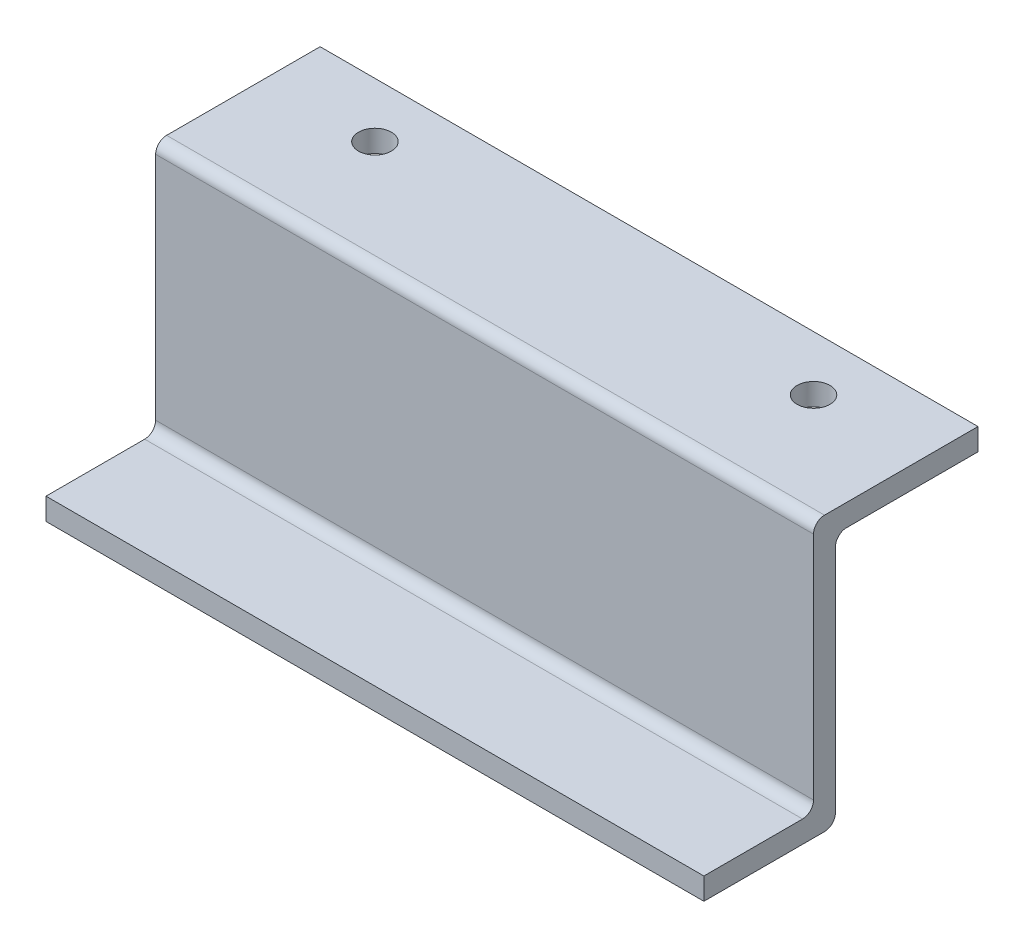
SolidWorks part; units mm, degrees
ref_plane "Front Plane" through (0, 0, 0) normal (0, 0, 1) x (1, 0, 0)
ref_plane "Top Plane" through (0, 0, 0) normal (0, 1, 0) x (1, 0, 0)
ref_plane "Right Plane" through (0, 0, 0) normal (1, 0, 0) x (0, 0, -1)
sketch "Sketch1" plane through (0, 0, 0) normal (1, 0, 0) x (0, 0, -1)
  line L0 (0, 0) -> (0, 2)
  line L1 (0, 0) -> (75, 0)
  line L2 (0, 0) -> (0, 25)
  line L3 (0, 25) -> (75, 25)
  line L4 (75, 0) -> (75, 25)
  line L5 (0, 2) -> (10, 2)
  line L6 (0, 0) -> (14.835, 0)
  line L7 (0, 0) -> (12, 0)
  line L8 (10, 2) -> (10, 25)
  line L9 (10, 25) -> (22, 25)
  line L11 (25, 23) -> (12, 23)
  line L12 (12, 23) -> (12, 0)
  line L13 (22, 25) -> (25, 25)
  line L14 (25, 25) -> (25, 23)
  dimension "D1" = 25
  dimension "D2" = 75
  dimension "D3" = 2
  dimension "D4" = 10
  dimension "D5" = 12
  dimension "D6" = 13
extrude "Boss-Extrude1" add sketch "Sketch1" along normal blind 60
fillet "Fillet1" radius 1 4 edges at (30, 2, -10) (30, 25, -10) (30, 23, -12) (30, 0, -12)
sketch "Sketch2" plane through (0, 25, 0) normal (0, 1, 0) x (1, 0, 0)
  line L0 (60, 25) -> (60, 20)
  line L1 (60, 11) -> (60, 25) construction
  line L2 (60, 20) -> (50, 20)
  line L3 (0, 25) -> (0, 20)
  line L4 (0, 11) -> (0, 25) construction
  line L5 (0, 20) -> (10, 20)
  circle A0 centre (10, 20) radius 1.5
  circle A1 centre (50, 20) radius 1.5
  dimension "D1" = 10
  dimension "D2" = 10
extrude "Cut-Extrude1" cut sketch "Sketch2" against normal blind 40
